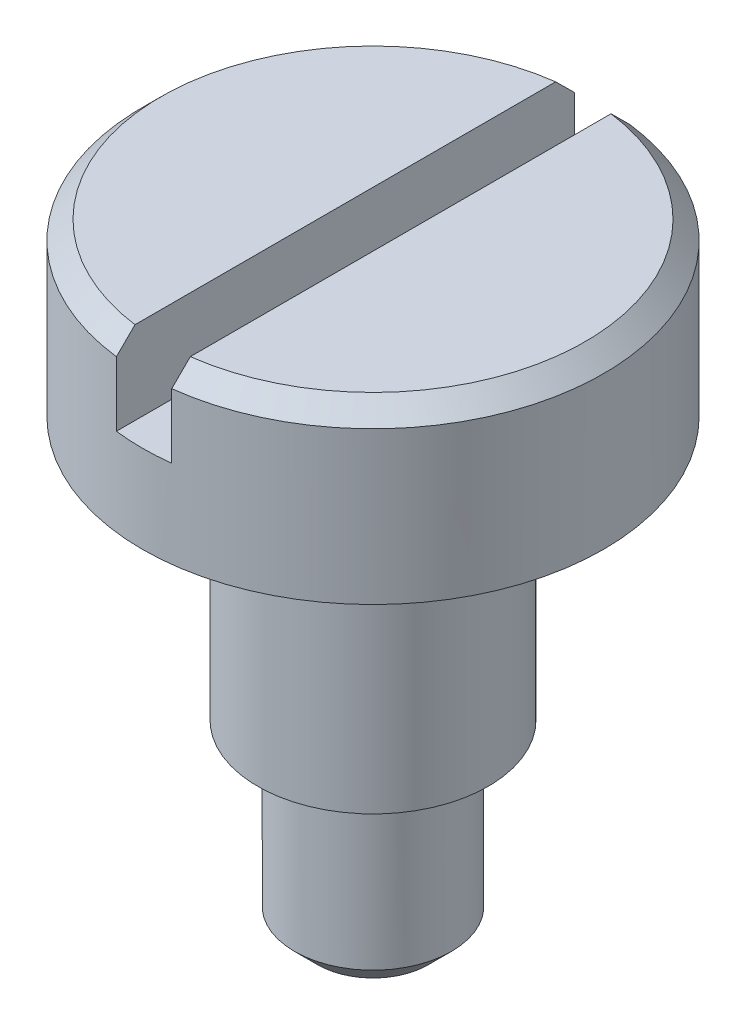
SolidWorks part; units mm, degrees
ref_plane "Front Plane" through (0, 0, 0) normal (0, 0, 1) x (1, 0, 0)
ref_plane "Top Plane" through (0, 0, 0) normal (0, 1, 0) x (1, 0, 0)
ref_plane "Right Plane" through (0, 0, 0) normal (1, 0, 0) x (0, 0, -1)
sketch "Sketch1" plane through (0, 0, 0) normal (0, 1, 0) x (1, 0, 0)
  circle A0 centre (0, 0) radius 2.5
  dimension "D1" = 5
extrude "Boss-Extrude1" add sketch "Sketch1" along normal blind 6.7
sketch "Sketch2" plane through (0, 0, 0) normal (0, -1, 0) x (1, 0, 0)
  circle A0 centre (0, 0) radius 0.85
  dimension "D1" = 1.7
extrude "Cut-Extrude1" cut sketch "Sketch2" against normal blind 2 flip side to cut
cosmetic thread "Cosmetic Thread1" parameters "D2"=1.202
sketch "Sketch3" plane through (0, 2, 0) normal (0, -1, 0) x (1, 0, 0)
  circle A0 centre (0, 0) radius 1.25
  dimension "D1" = 2.5
extrude "Cut-Extrude2" cut sketch "Sketch3" against normal blind 2.85 flip side to cut
chamfer "Chamfer1" distance 0.2 angle 45 1 edges at (0, 6.7, 2.5)
sketch "Sketch4" plane through (0, 0, 0) normal (0, 0, 1) x (1, 0, 0)
  line L0 (0, 0) -> (0, 6.7) construction
  line L1 (2.3, 6.7) -> (-2.3, 6.7) construction
  line L3 (-0.3, 6.7) -> (0.3, 6.7)
  line L4 (-0.3, 6.7) -> (-0.3, 5.8)
  line L5 (-0.3, 5.8) -> (0.3, 5.8)
  line L6 (0.3, 6.7) -> (0.3, 5.8)
  dimension "D1" = 0.6
  dimension "D2" = 0.9
extrude "Cut-Extrude3" cut sketch "Sketch4" against normal through all both and the other way through all
chamfer "Chamfer2" distance 0.25 angle 45 1 edges at (0, 0, -0.85)
